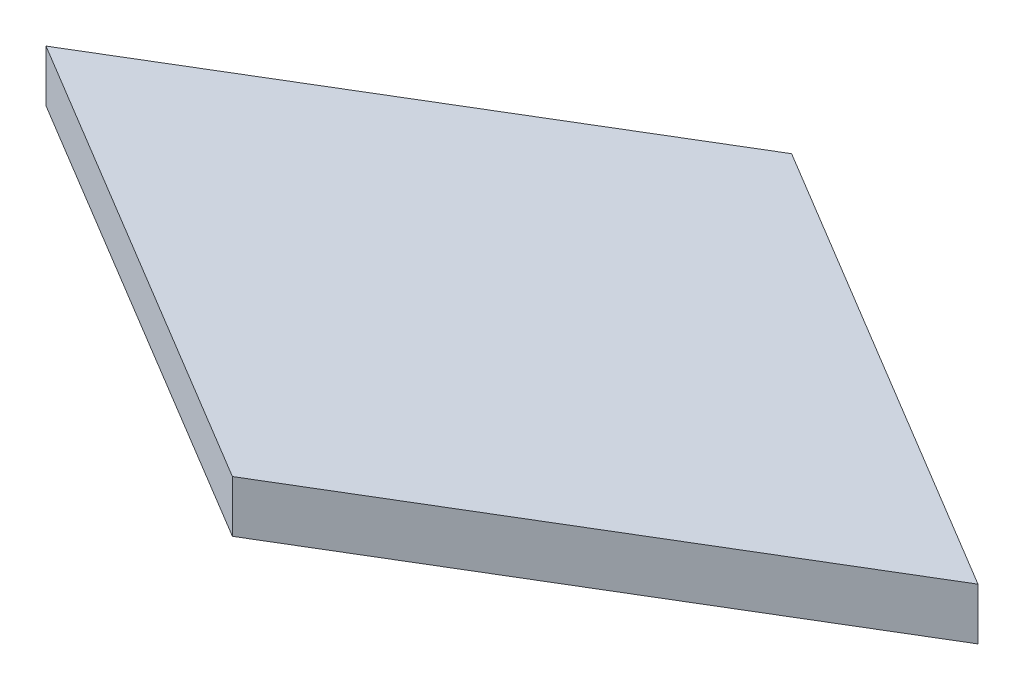
SolidWorks part; units mm, degrees
material "普通碳钢"
ref_plane "前视基准面" through (0, 0, 0) normal (0, 0, 1) x (1, 0, 0)
ref_plane "上视基准面" through (0, 0, 0) normal (0, 1, 0) x (1, 0, 0)
ref_plane "右视基准面" through (0, 0, 0) normal (1, 0, 0) x (0, 0, -1)
other "Configuration Table"
sketch "草图1" plane through (0, 0, 0) normal (0, 1, 0) x (1, 0, 0)
  line L0 (0, 0) -> (0, 27) construction
  line L1 (0, 0) -> (45, 0) construction
  line L2 (45, 0) -> (0, 27)
  line L3 (45, 0) -> (0, -27)
  line L4 (-45, 0) -> (0, -27)
  line L5 (-45, 0) -> (0, 27)
  dimension "D1" = 27
  dimension "D2" = 45
extrude "凸台-拉伸1" add sketch "草图1" along normal blind 5
